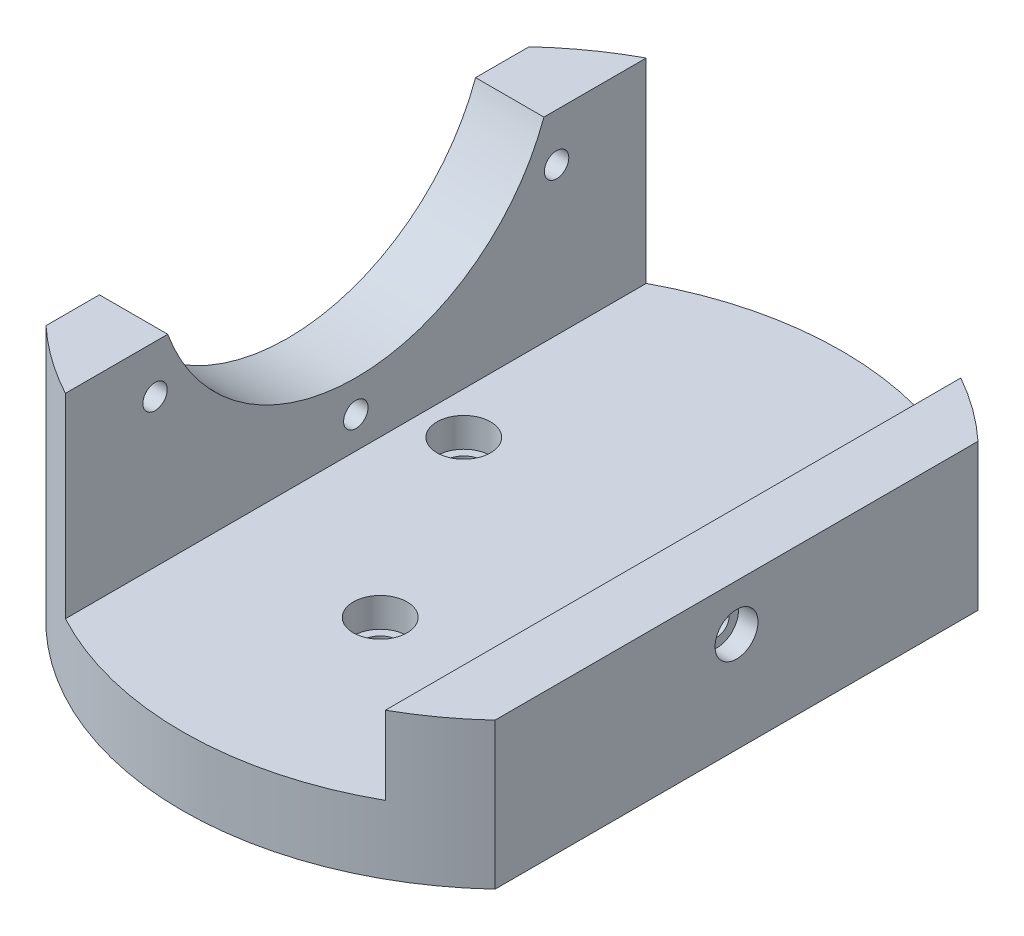
SolidWorks part; units mm, degrees
ref_plane "Front Plane" through (0, 0, 0) normal (0, 0, 1) x (1, 0, 0)
ref_plane "Top Plane" through (0, 0, 0) normal (0, 1, 0) x (1, 0, 0)
ref_plane "Right Plane" through (0, 0, 0) normal (1, 0, 0) x (0, 0, -1)
sketch "Sketch8" plane through (0, 0, 0) normal (0, 1, 0) x (1, 0, 0)
  line L0 (-23, 24.7391) -> (-23, -24.7391)
  line L1 (23, -24.7391) -> (23, 24.7391)
  arc A0 (-23, -24.7391) -> (23, -24.7391) centre (0, 0) ccw
  circle A2 centre (11.6913, 6.75) radius 1.912
  circle A4 centre (0, -13.5) radius 1.912
  circle A6 centre (-11.6913, 6.75) radius 1.912
  arc A7 (23, 24.7391) -> (-23, 24.7391) centre (0, 0) ccw
  point P18 (0, 0)
  dimension "D1" = 46
  dimension "D2" = 23
extrude "Boss-Extrude7" add sketch "Sketch8" along normal blind 7
sketch "Sketch9" plane through (0, 7, 0) normal (0, 1, 0) x (1, 0, 0)
  circle A0 centre (-11.6913, 6.75) radius 2.75
  circle A1 centre (11.6913, 6.75) radius 2.75
  circle A2 centre (0, -13.5) radius 2.75
extrude "Cut-Extrude4" cut sketch "Sketch9" against normal blind 3
sketch "Sketch12" plane through (0, 7, 0) normal (0, 1, 0) x (1, 0, 0)
  line L0 (-16, 29.7493) -> (-16, -29.7493)
  line L1 (-23, 24.7391) -> (-23, -24.7391) construction
  line L2 (-23, 24.7391) -> (-23, -24.7391)
  arc A0 (23, 24.7391) -> (-23, 24.7391) centre (0, 0) ccw construction
  arc A1 (-23, -24.7391) -> (23, -24.7391) centre (0, 0) ccw construction
  arc A2 (-23, -24.7391) -> (-16, -29.7493) centre (0, 0) ccw
  arc A3 (-16, 29.7493) -> (-23, 24.7391) centre (0, 0) ccw
  dimension "D1" = 7
extrude "Boss-Extrude9" add sketch "Sketch12" along normal blind 20
sketch "Sketch13" plane through (-16, 0, 0) normal (1, 0, 0) x (0, 0, -1)
  line L0 (-29.7493, 27) -> (29.7493, 27) construction
  circle A0 centre (0, 34) radius 20.5
  dimension "D2" = 0
  dimension "D1" = 7
extrude "Cut-Extrude7" cut sketch "Sketch13" against normal blind 19.5
sketch "Sketch14" plane through (-16, 0, 0) normal (1, 0, 0) x (0, 0, -1)
  circle A0 centre (0, 10.25) radius 1.25
  circle A7 centre (-20.5681, 22.125) radius 1.25
  arc A10 (-19.2678, 27) -> (19.2678, 27) centre (0, 34) ccw construction
  circle A12 centre (20.5681, 22.125) radius 1.25
  circle A13 centre (-20.5681, 45.875) radius 1.25 [skipped]
  circle A14 centre (0, 57.75) radius 1.25 [skipped]
  circle A15 centre (20.5681, 45.875) radius 1.25 [skipped]
  point P18 (0, 34)
  point P19 (-0.433, 33.75)
  dimension "D1" = 23.75
  dimension "D2" = 6
extrude "Cut-Extrude8" cut sketch "Sketch14" against normal blind 19.5
sketch "Sketch15" plane through (-23, 0, 0) normal (-1, 0, 0) x (0, 0, 1)
  circle A1 centre (0, 10.25) radius 2.2
  circle A3 centre (-20.5681, 22.125) radius 2.2
  circle A4 centre (20.5681, 22.125) radius 2.2
extrude "Cut-Extrude9" cut sketch "Sketch15" against normal blind 2
sketch "Sketch16" plane through (0, 7, 0) normal (0, 1, 0) x (1, 0, 0)
  line L0 (16.5, 29.4749) -> (16.5, -29.4749)
  line L1 (23, -24.7391) -> (23, 24.7391) construction
  line L2 (23, 24.7391) -> (23, -24.7391)
  arc A0 (23, 24.7391) -> (-16, 29.7493) centre (0, 0) ccw construction
  arc A1 (-16, -29.7493) -> (23, -24.7391) centre (0, 0) ccw construction
  arc A2 (16.5, -29.4749) -> (23, -24.7391) centre (0, 0) ccw
  arc A3 (23, 24.7391) -> (16.5, 29.4749) centre (0, 0) ccw
  dimension "D1" = 6.5
extrude "Boss-Extrude10" add sketch "Sketch16" along normal blind 8
sketch "Sketch17" plane through (23, 0, 0) normal (1, 0, 0) x (0, 0, -1)
  circle A0 centre (0, 10.25) radius 1.25
  arc A1 (-19.2678, 27) -> (19.2678, 27) centre (0, 34) ccw construction
  dimension "D1" = 23.75
extrude "Cut-Extrude10" cut sketch "Sketch17" against normal blind 7.5
sketch "Sketch18" plane through (23, 0, 0) normal (1, 0, 0) x (0, 0, -1)
  circle A0 centre (0, 10.25) radius 2.2
extrude "Cut-Extrude11" cut sketch "Sketch18" against normal blind 2
